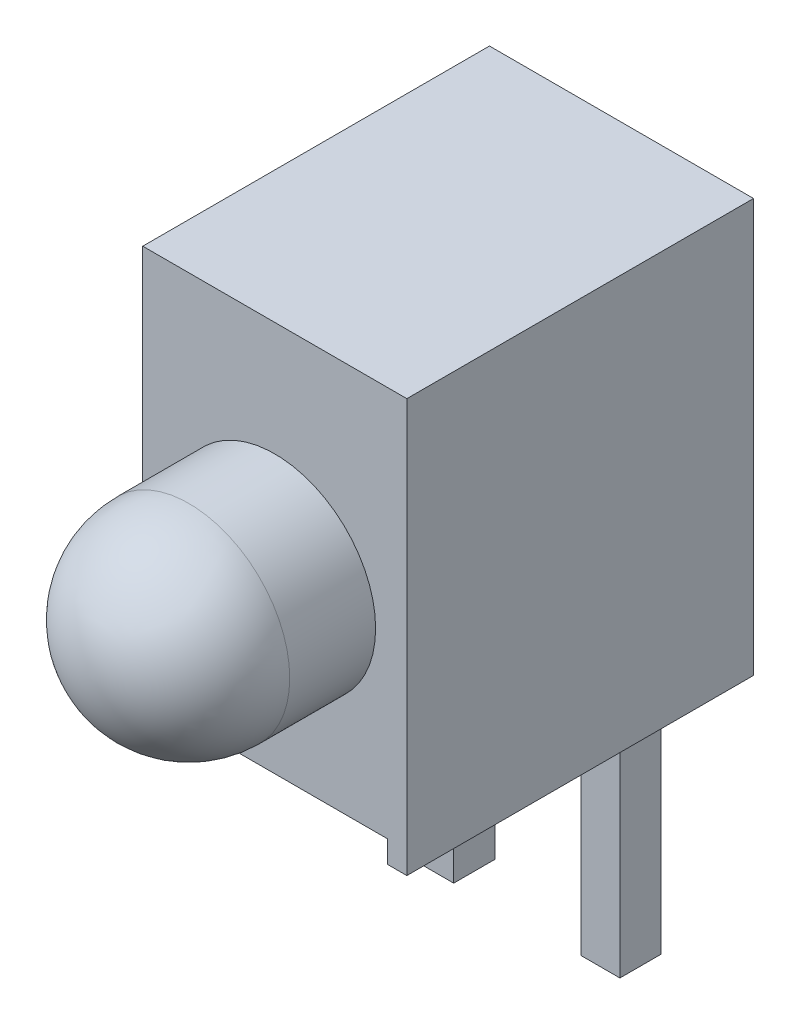
SolidWorks part; units mm, degrees
ref_plane "Front Plane" through (0, 0, 0) normal (0, 0, 1) x (1, 0, 0)
ref_plane "Top Plane" through (0, 0, 0) normal (0, 1, 0) x (1, 0, 0)
ref_plane "Right Plane" through (0, 0, 0) normal (1, 0, 0) x (0, 0, -1)
sketch "Sketch1" plane through (0, 0, 0) normal (0, 1, 0) x (1, 0, 0)
  line L1 (-2.03, 2.665) -> (2.03, 2.665)
  line L2 (-2.03, 2.665) -> (-2.03, -2.665)
  line L3 (-2.03, -2.665) -> (2.03, -2.665)
  line L4 (2.03, 2.665) -> (2.03, -2.665)
  line L5 (-2.03, 2.665) -> (2.03, -2.665) construction
  line L6 (-2.03, -2.665) -> (2.03, 2.665) construction
  point P0 (0, 0)
  dimension "D1" = 4.06
  dimension "D2" = 5.33
extrude "Boss-Extrude1" add sketch "Sketch1" along normal blind 6.35
sketch "Sketch2" plane through (0, 0, 2.665) normal (0, 0, 1) x (1, 0, 0)
  line L0 (-2.03, 0) -> (2.03, 0) construction
  circle A0 centre (0, 3.05) radius 1.55
  dimension "D2" = 3.1
  dimension "D3" = 3.05
extrude "Boss-Extrude2" add sketch "Sketch2" along normal blind 2.8702
fillet "Fillet2" radius 1.55 1 edges at (1.55, 3.05, 5.5352)
sketch "Sketch4" plane through (0, 0, 2.665) normal (0, 0, 1) x (1, 0, 0)
  line L0 (-2.03, 0) -> (2.03, 0) construction
  line L1 (-1.7627, 0) -> (1.7312, 0)
  line L2 (-1.7627, 0) -> (-1.7627, 0.3407)
  line L3 (-1.7627, 0.3407) -> (1.7312, 0.3407)
  line L4 (1.7312, 0) -> (1.7312, 0.3407)
extrude "Cut-Extrude1" cut sketch "Sketch4" against normal through all
sketch "Sketch6" plane through (0, 0.3407, 0) normal (0, -1, 0) x (1, 0, 0)
  line L0 (1.7312, 2.665) -> (2.03, 2.665) construction
  line L1 (-1.5782, -1.0636) -> (-0.9782, -1.0636)
  line L2 (-1.5782, -1.0636) -> (-1.5782, -1.6964)
  line L3 (-1.5782, -1.6964) -> (-0.9782, -1.6964)
  line L4 (-0.9782, -1.0636) -> (-0.9782, -1.6964)
  line L5 (-1.5782, -1.0636) -> (-0.9782, -1.6964) construction
  line L6 (-1.5782, -1.6964) -> (-0.9782, -1.0636) construction
  line L7 (0.9618, -1.0786) -> (1.5618, -1.0786)
  line L8 (0.9618, -1.0786) -> (0.9618, -1.7114)
  line L9 (0.9618, -1.7114) -> (1.5618, -1.7114)
  line L10 (1.5618, -1.0786) -> (1.5618, -1.7114)
  line L11 (0.9618, -1.0786) -> (1.5618, -1.7114) construction
  line L12 (0.9618, -1.7114) -> (1.5618, -1.0786) construction
  line L13 (0, 0) -> (-0.0157, -2.665) construction
  line L14 (1.7312, -2.665) -> (-1.7627, -2.665) construction
  point P0 (-1.2782, -1.38)
  point P5 (1.2618, -1.395)
  dimension "D1" = 4.06
  dimension "D2" = 2.54
  dimension "D3" = 0.6
  dimension "D4" = 0.6
extrude "Boss-Extrude5" add sketch "Sketch6" along normal blind 3.81
